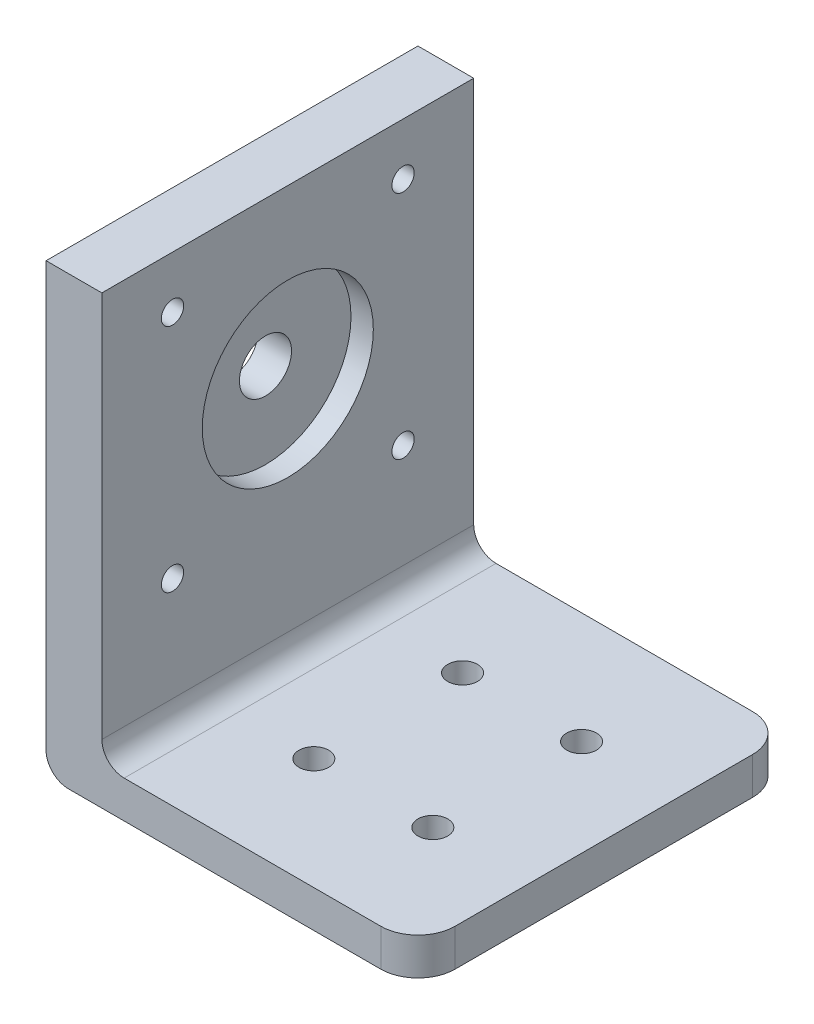
SolidWorks part; units mm, degrees
ref_plane "Front Plane" through (0, 0, 0) normal (0, 0, 1) x (1, 0, 0)
ref_plane "Top Plane" through (0, 0, 0) normal (0, 1, 0) x (1, 0, 0)
ref_plane "Right Plane" through (0, 0, 0) normal (1, 0, 0) x (0, 0, -1)
sketch "Sketch1" plane through (0, 0, 0) normal (0, 1, 0) x (1, 0, 0)
  line L5 (-25, 25) -> (20, 25)
  line L6 (-25, 25) -> (-25, -25)
  line L7 (-25, -25) -> (20, -25)
  line L8 (25, 20) -> (25, -20)
  line L9 (-25, 25) -> (25, -25) construction
  line L10 (-25, -25) -> (25, 25) construction
  arc A0 (20, -25) -> (25, -20) centre (20, -20) ccw
  arc A1 (20, 25) -> (25, 20) centre (20, 20) cw
  point P0 (0, 0)
  dimension "D3" = 5
  dimension "D1" = 50
  dimension "D2" = 50
extrude "Boss-Extrude1" add sketch "Sketch1" along normal blind 5
sketch "Sketch2" plane through (0, 5, 0) normal (0, 1, 0) x (1, 0, 0)
  line L0 (-25, -25) -> (20, -25) construction
  line L1 (-25, 25) -> (-17.5, 25)
  line L2 (-25, 25) -> (-25, -25)
  line L3 (-25, -25) -> (-17.5, -25)
  line L4 (-17.5, 25) -> (-17.5, -25)
  dimension "D1" = 7.5
extrude "Boss-Extrude2" add sketch "Sketch2" along normal blind 55 contours L2 L1 L4 L3
fillet "Fillet1" radius 3 1 edges at (-17.5, 5, 0)
fillet "Fillet2" radius 3 1 edges at (-25, 0, 0)
sketch "Sketch3" plane through (-25, 0, 0) normal (-1, 0, 0) x (0, 0, 1)
  line L0 (-25, 60) -> (25, 60) construction
  line L1 (0, 0) -> (0, 60) construction
  line L2 (0, 37.5) -> (19.1303, 37.5) construction
  circle A1 centre (15.5, 53) radius 1.5
  circle A2 centre (-15.5, 53) radius 1.5
  circle A3 centre (0, 37.5) radius 3.5
  circle A4 centre (15.5, 22) radius 1.5
  circle A5 centre (-15.5, 22) radius 1.5
  point P0 (15.5, 53)
  dimension "D3" = 3
  dimension "D4" = 7
  dimension "D1" = 7
  dimension "D2" = 15.5
  dimension "D5" = 15.5
extrude "Cut-Extrude1" cut sketch "Sketch3" against normal through all
sketch "Sketch4" plane through (-17.5, 0, 0) normal (1, 0, 0) x (0, 0, -1)
  circle A0 centre (0, 37.5) radius 11.5
  dimension "D1" = 23
extrude "Cut-Extrude2" cut sketch "Sketch4" against normal blind 3
sketch "Sketch6" plane through (0, 5, 0) normal (0, 1, 0) x (1, 0, 0)
  line L0 (-14.5, 0) -> (27.1908, 0) construction
  line L2 (-25, 25) -> (-25, -25) construction
  circle A0 centre (12, -10) radius 2
  circle A1 centre (-4, -10) radius 2
  circle A2 centre (12, 10) radius 2
  circle A3 centre (-4, 10) radius 2
  point P9 (12, -10)
  point P10 (-4, -10)
  dimension "D1" = 21
  dimension "D2" = 16
  dimension "D3" = 10
extrude "Cut-Extrude3" cut sketch "Sketch6" against normal through all
